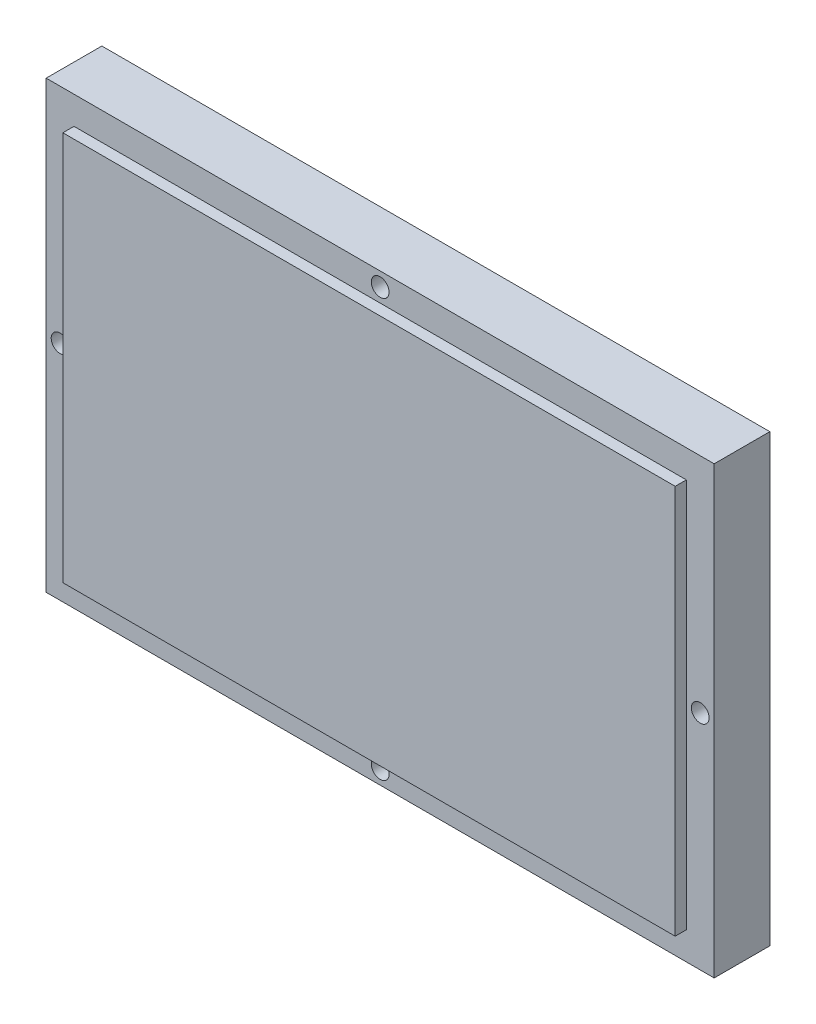
SolidWorks part; units mm, degrees
ref_plane "Front Plane" through (0, 0, 0) normal (0, 0, 1) x (1, 0, 0)
ref_plane "Top Plane" through (0, 0, 0) normal (0, 1, 0) x (1, 0, 0)
ref_plane "Right Plane" through (0, 0, 0) normal (1, 0, 0) x (0, 0, -1)
sketch "Sketch1" plane through (0, 0, 0) normal (0, 0, 1) x (1, 0, 0)
  line L1 (0, 0) -> (76.2, 0)
  line L2 (0, 0) -> (0, 50.8)
  line L3 (0, 50.8) -> (76.2, 50.8)
  line L4 (76.2, 0) -> (76.2, 50.8)
  dimension "D1" = 50.8
  dimension "D2" = 76.2
extrude "Boss-Extrude1" add sketch "Sketch1" along normal blind 7.62
sketch "Sketch4" plane through (0, 0, 7.62) normal (0, 0, 1) x (1, 0, 0)
  line L0 (38.1, 50.8) -> (38.1, 0)
  line L1 (76.2, 50.8) -> (0, 50.8) construction
  line L2 (0, 0) -> (76.2, 0) construction
  line L4 (3.175, 3.175) -> (73.025, 3.175)
  line L5 (3.175, 3.175) -> (3.175, 47.625)
  line L6 (3.175, 47.625) -> (73.025, 47.625)
  line L7 (73.025, 3.175) -> (73.025, 47.625)
  line L8 (3.175, 3.175) -> (73.025, 47.625) construction
  line L9 (3.175, 47.625) -> (73.025, 3.175) construction
  line L10 (0, 50.8) -> (76.2, 50.8)
  line L11 (0, 50.8) -> (0, 0)
  line L12 (0, 0) -> (76.2, 0)
  line L13 (76.2, 50.8) -> (76.2, 0)
  point P6 (38.1, 25.4)
  line M3 (0, 50.8) -> (0, 0)
  line M4 (0, 0) -> (76.2, 0)
  line M5 (76.2, 0) -> (76.2, 50.8)
  line M6 (76.2, 50.8) -> (0, 50.8)
  dimension "D1" = 69.85
  dimension "D2" = 44.45
extrude "Cut-Extrude3" cut sketch "Sketch4" against normal blind 1.27 contours L5 L6 L0 L4 M6 M3 M4 | L7 L4 L0 L6 M4 M5 M6
sketch "Sketch5" plane through (0, 0, 6.35) normal (0, 0, 1) x (1, 0, 0)
  circle A0 centre (1.5875, 25.4) radius 1.016
  circle A1 centre (38.1, 49.2125) radius 1.016
  circle A2 centre (74.6125, 25.4) radius 1.016
  circle A3 centre (38.1, 1.5875) radius 1.016
  dimension "D1" = 2.032
extrude "Cut-Extrude4" cut sketch "Sketch5" against normal through all
